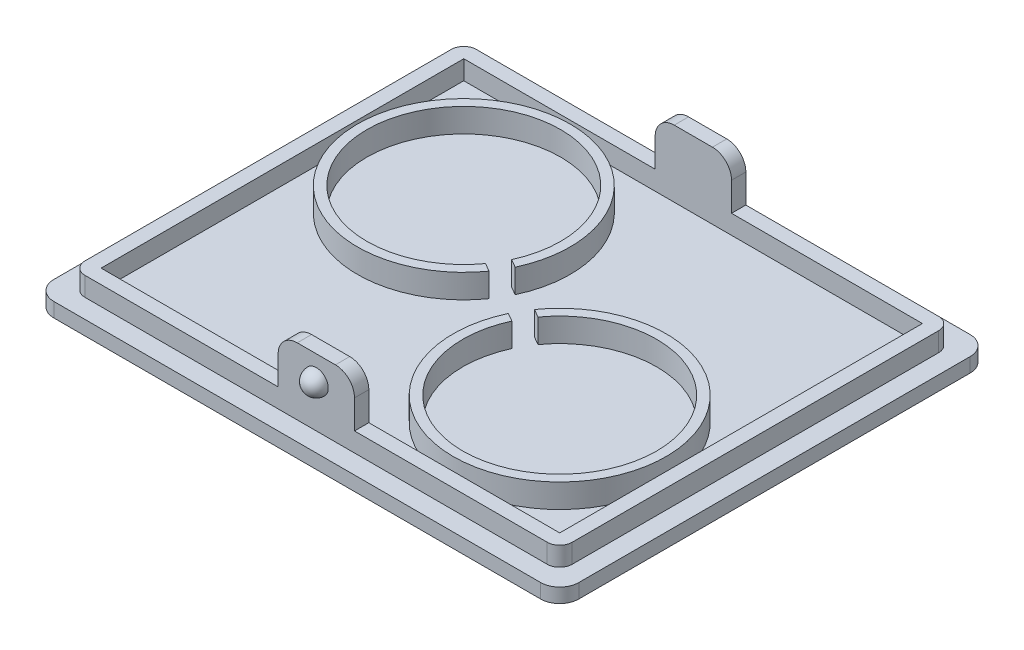
SolidWorks part; units mm, degrees
ref_plane "Front" through (0, 0, 0) normal (0, 0, 1) x (1, 0, 0)
ref_plane "Top" through (0, 0, 0) normal (0, 1, 0) x (1, 0, 0)
ref_plane "Right" through (0, 0, 0) normal (1, 0, 0) x (0, 0, -1)
sketch "Croquis1" plane through (0, 0, 0) normal (0, 1, 0) x (1, 0, 0)
  line L1 (-25.5, -22.5) -> (25.5, -22.5)
  line L2 (-27.5, -20.5) -> (-27.5, 20.5)
  line L3 (-25.5, 22.5) -> (25.5, 22.5)
  line L4 (27.5, -20.5) -> (27.5, 20.5)
  line L5 (-27.5, -22.5) -> (27.5, 22.5) construction
  line L6 (-27.5, 22.5) -> (27.5, -22.5) construction
  arc A0 (-25.5, 22.5) -> (-27.5, 20.5) centre (-25.5, 20.5) ccw
  arc A1 (27.5, 20.5) -> (25.5, 22.5) centre (25.5, 20.5) ccw
  arc A2 (25.5, -22.5) -> (27.5, -20.5) centre (25.5, -20.5) ccw
  arc A3 (-27.5, -20.5) -> (-25.5, -22.5) centre (-25.5, -20.5) ccw
  point P0 (0, 0)
  dimension "D3" = 2
  dimension "D4" = 2
  dimension "D5" = 2
  dimension "D6" = 2
  dimension "D1" = 55
  dimension "D2" = 45
extrude "Saliente-Extruir1" add sketch "Croquis1" along normal blind 1.5
sketch "Croquis9" plane through (0, 1.5, 0) normal (0, 1, 0) x (1, 0, 0)
  line L0 (-1000, 0) -> (49000, 0) construction
  line L1 (0, -1000) -> (0, 49000) construction
  line L2 (-27.5, -979.5) -> (-27.5, 49020.5) construction
  line L3 (27.5, -979.5) -> (27.5, 49020.5) construction
  line L4 (-974.5, 22.5) -> (49025.5, 22.5) construction
  line L5 (-974.5, -22.5) -> (49025.5, -22.5) construction
  line L6 (-1027.5, 20.5) -> (48972.5, 20.5) construction
  line L7 (-1027.5, -20.5) -> (48972.5, -20.5) construction
  line L8 (-25.5, -977.5) -> (-25.5, 49022.5) construction
  line L9 (25.5, -977.5) -> (25.5, 49022.5) construction
  line L10 (-24.0513, 19) -> (24, 19)
  line L11 (-24.2438, 20.5) -> (24.1925, 20.5)
  line L12 (-25.5513, 19.1925) -> (-25.5513, -19.1925)
  line L13 (-24.2438, -20.5) -> (24.1925, -20.5)
  line L14 (25.5, 19.1925) -> (25.5, -19.1925)
  line L15 (24, 19) -> (24, -19)
  line L16 (-24.0513, -19) -> (24, -19)
  line L17 (-24.0513, 19) -> (-24.0513, -19)
  arc A0 (-24.2438, 20.5) -> (-25.5513, 19.1925) centre (-24.2438, 19.1925) ccw
  arc A1 (-25.5513, -19.1925) -> (-24.2438, -20.5) centre (-24.2438, -19.1925) ccw
  arc A2 (24.1925, -20.5) -> (25.5, -19.1925) centre (24.1925, -19.1925) ccw
  arc A3 (25.5, 19.1925) -> (24.1925, 20.5) centre (24.1925, 19.1925) ccw
  arc A4 (24, 19) -> (24, 19) centre (24, 19) ccw
  arc A5 (24, -19) -> (24, -19) centre (24, -19) ccw
  arc A6 (-24.0513, -19) -> (-24.0513, -19) centre (-24.0513, -19) ccw
  arc A7 (-24.0513, 19) -> (-24.0513, 19) centre (-24.0513, 19) ccw
  point P33 (-25.5513, 20.5)
  point P38 (25.5, -20.5)
  dimension "D1" = 1.3075
  dimension "D2" = 1.5
extrude "Saliente-Extruir7" add sketch "Croquis9" along normal blind 2
sketch "Croquis10" plane through (0, 3.5, 0) normal (0, 1, 0) x (1, 0, 0)
  line L0 (-1000, 0) -> (49000, 0) construction
  line L1 (0, -1000) -> (0, 49000) construction
  line L2 (24.1925, 20.5) -> (-24.2438, 20.5) construction
  line L3 (-4, 20.5) -> (4, 20.5)
  line L4 (-4, 20.5) -> (-4, 19)
  line L5 (-4, 19) -> (4, 19)
  line L6 (4, 20.5) -> (4, 19)
  line L7 (24, 19) -> (-24.0513, 19) construction
  line L8 (-4, -20.5) -> (-4, -19)
  line L9 (-4, -19) -> (4, -19)
  line L10 (4, -20.5) -> (4, -19)
  line L11 (-4, -20.5) -> (4, -20.5)
  dimension "D1" = 8
  dimension "D2" = 4
extrude "Saliente-Extruir8" add sketch "Croquis10" along normal blind 5
fillet "Redondeo1" radius 2 4 edges at (4, 8.5, 19.75) (-4, 8.5, 19.75) (-4, 8.5, -19.75) (4, 8.5, -19.75)
sketch "Croquis11" plane through (0, 0, -20.5) normal (0, 0, -1) x (-1, 0, 0)
  line L0 (0, -991.5) -> (0, 49008.5) construction
  line L1 (-2, 8.5) -> (2, 8.5) construction
  line L2 (-1000, 6) -> (49000, 6) construction
  line L3 (-24.1925, 3.5) -> (-4, 3.5) construction
  circle A0 centre (0, 6) radius 1.625
  point P5 (0, 8.5)
  dimension "D2" = 3.25
  dimension "D1" = 2.5
extrude "Cortar-Extruir3" [suppressed] cut sketch "Croquis11" against normal up to surface (41 mm away)
sketch "Croquis12" plane through (0, 1.5, 0) normal (0, 1, 0) x (1, 0, 0)
  line L0 (-1000, 0) -> (49000, 0) construction
sketch "Croquis13" plane through (0, 0, 20.5) normal (0, 0, 1) x (1, 0, 0)
  line L0 (0, -1000) -> (0, 49000) construction
  line L2 (0, 7.25) -> (0, 4.75)
  line L3 (-401000, 6) -> (449000, 6)
  line L4 (-401000, 6) -> (449000, 6) construction
  arc A0 (0, 7.25) -> (0, 4.75) centre (0, 6) ccw
  dimension "D2" = 1.25
  dimension "D1" = 4.5
revolve "Revolución1" add sketch "Croquis13" angle 180 about L0
ref_plane "Plano3" through (0, 0, 0) normal (0, 0, 1) x (1, 0, 0)
mirror "Simetría1" about plane through (0, 0, 0) normal (0, 0, 1) of "Revolución1"
sketch "Croquis14" plane through (0, 1.5, 0) normal (0, 1, 0) x (1, 0, 0)
  line L0 (-1000, 0) -> (49000, 0) construction
  line L1 (0, -1000) -> (0, 49000) construction
  line L2 (-24.0513, 19) -> (-24.0513, -19) construction
  line L3 (-24.0513, -19) -> (24, -19) construction
  line L4 (24, -19) -> (24, 19) construction
  line L6 (24, 19) -> (4, 19) construction
  line L7 (11.9987, -1007) -> (11.9987, 48993) construction
  line L8 (-12.05, -993) -> (-12.05, 49007) construction
  circle A0 centre (11.9987, -7) radius 10.15
  circle A1 centre (-12.05, 7) radius 10.15
  circle A2 centre (11.9987, -7) radius 11.15
  circle A3 centre (-12.05, 7) radius 11.15
  dimension "D1" = 20.3
  dimension "D2" = 20.3
  dimension "D3" = 36.05
  dimension "D4" = 12
  dimension "D5" = 36.05
  dimension "D6" = 12
  dimension "D7" = 1
extrude "Saliente-Extruir9" add sketch "Croquis14" along normal blind 2.5
sketch "Croquis15" plane through (0, 1.5, 0) normal (0, 1, 0) x (1, 0, 0)
  line L0 (0, -1000) -> (0, 49000) construction
  line L1 (-1000, 0) -> (49000, 0) construction
  line L2 (-12.05, 7) -> (11.9987, -7) construction
  line L3 (-12.5531, 6.1358) -> (11.4955, -7.8642)
  line L4 (-11.5469, 7.8642) -> (12.5018, -6.1358)
  line L5 (11.4955, -7.8642) -> (12.5018, -6.1358)
  line L6 (-12.5531, 6.1358) -> (-11.5469, 7.8642)
  line L7 (-11.5469, 7.8642) -> (12.8313, 6.0969)
  circle M2 centre (-12.05, 7) radius 11.15
  circle M3 centre (11.9987, -7) radius 11.15
  dimension "D1" = 1
  dimension "D2" = 1
extrude "Cortar-Extruir4" cut sketch "Croquis15" along normal blind 2.5 contours L4 L3 M2 M3 | L6 L3 L4 M2 | L3 L5 L4 M3
